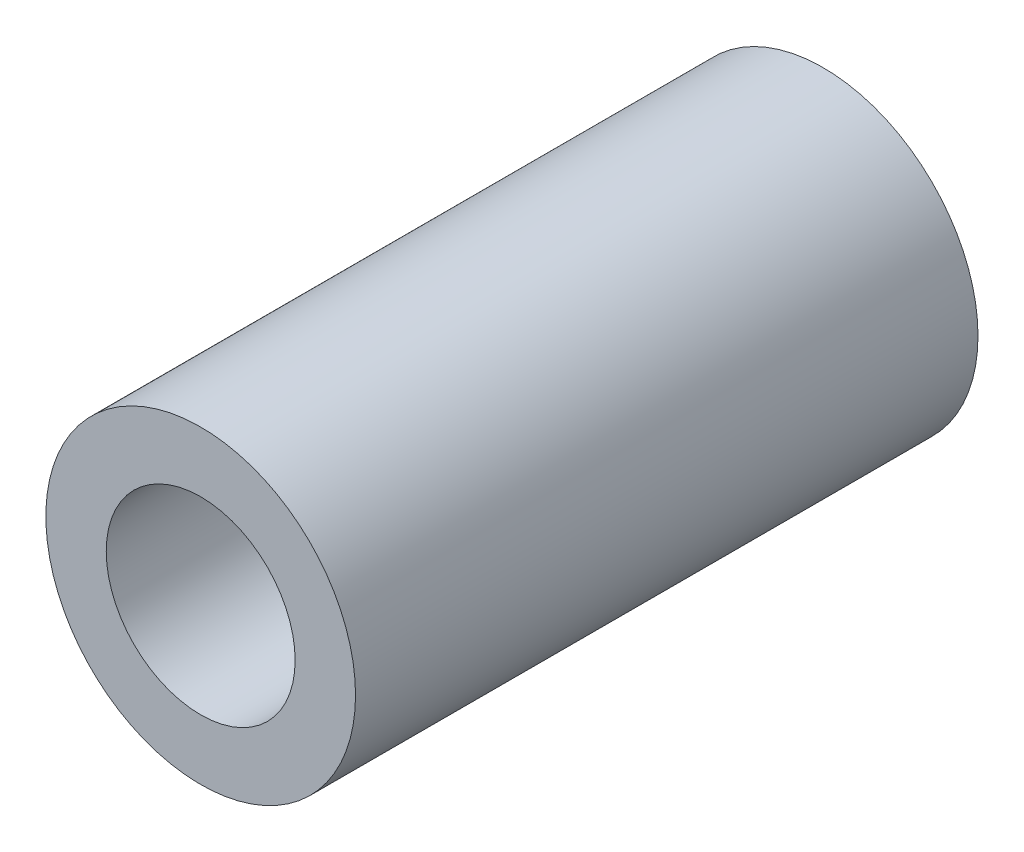
SolidWorks part; units mm, degrees
ref_plane "Plan de face" through (0, 0, 0) normal (0, 0, 1) x (1, 0, 0)
ref_plane "Plan de dessus" through (0, 0, 0) normal (0, 1, 0) x (1, 0, 0)
ref_plane "Plan de droite" through (0, 0, 0) normal (1, 0, 0) x (0, 0, -1)
sketch "Sketch1" plane through (0, 0, 0) normal (0, 0, 1) x (1, 0, 0)
  circle A0 centre (0, 0) radius 6.1
  circle A1 centre (0, 0) radius 10
  dimension "D1" = 12.2
  dimension "D2" = 20
extrude "Boss-Extrude1" add sketch "Sketch1" along normal mid plane 40.2
